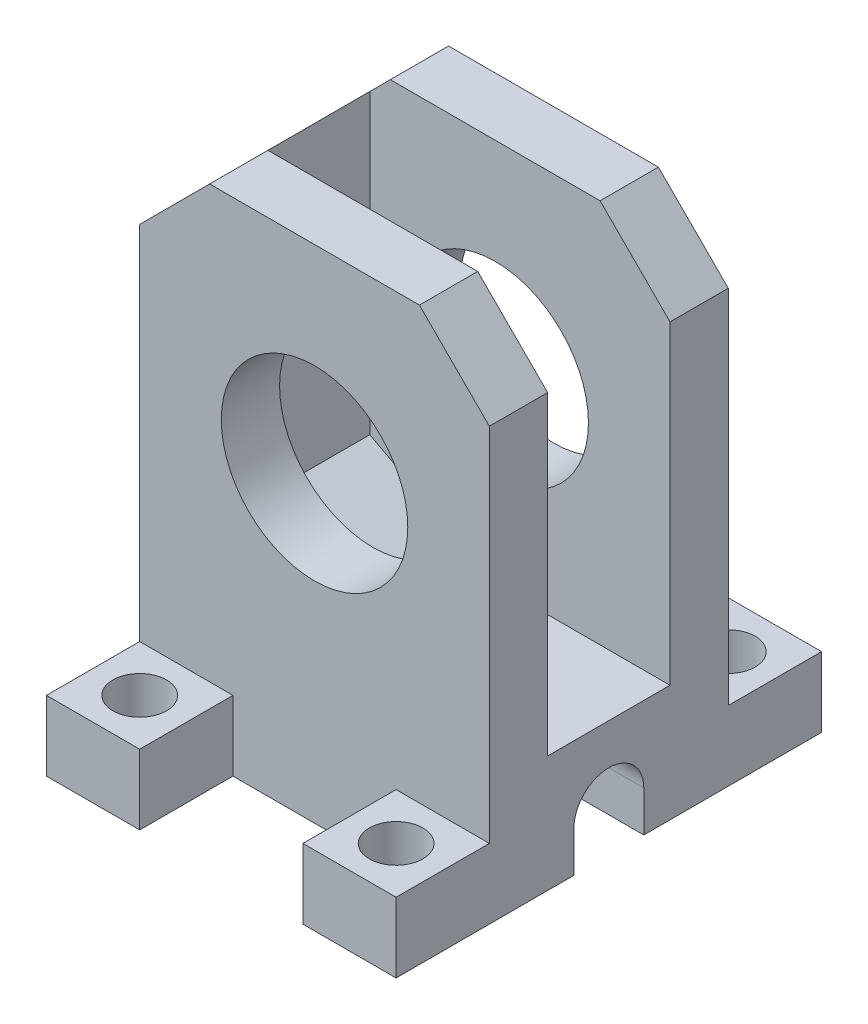
SolidWorks part; units mm, degrees
ref_plane "Plan de face" through (0, 0, 0) normal (0, 0, 1) x (1, 0, 0)
ref_plane "Plan de dessus" through (0, 0, 0) normal (0, 1, 0) x (1, 0, 0)
ref_plane "Plan de droite" through (0, 0, 0) normal (1, 0, 0) x (0, 0, -1)
sketch "Esquisse1" plane through (0, 0, 0) normal (0, 0, 1) x (1, 0, 0)
  line L0 (0, 0) -> (15, 0)
  line L1 (0, 0) -> (-15, 0)
  line L2 (-15, 0) -> (-15, 45)
  line L3 (-15, 45) -> (15, 45)
  line L4 (15, 45) -> (15, 0)
  line L5 (0, 0) -> (0, 28) construction
  circle A0 centre (0, 28) radius 8
  dimension "D1" = 28
extrude "Boss.-Extru.1" add sketch "Esquisse1" against normal blind 5
sketch "Esquisse2" plane through (0, 0, -5) normal (0, 0, -1) x (-1, 0, 0)
  line L0 (-15, 0) -> (15, 0)
  line L1 (15, 0) -> (15, 12)
  line L2 (15, 45) -> (15, 0) construction
  line L3 (15, 12) -> (-15, 12)
  line L4 (-15, 0) -> (-15, 45) construction
  line L5 (-15, 12) -> (-15, 0)
extrude "Boss.-Extru.2" add sketch "Esquisse2" along normal blind 10.5
sketch "Esquisse4" plane through (0, 0, 0) normal (0, -1, 0) x (1, 0, 0)
  line L0 (-15, -15.5) -> (15, -15.5)
  line L1 (15, -15.5) -> (15, -20.5)
  line L2 (15, -20.5) -> (-15, -20.5)
  line L3 (-15, -20.5) -> (-15, -15.5)
extrude "Boss.-Extru.3" add sketch "Esquisse4" against normal blind 45
sketch "Esquisse6" plane through (0, 0, -20.5) normal (0, 0, -1) x (-1, 0, 0)
  line L0 (0, 0) -> (0, 28) construction
  circle A1 centre (0, 28) radius 8
extrude "Enlèv. mat.-Extru.3" cut sketch "Esquisse6" against normal blind 10
sketch "Esquisse8" plane through (0, 0, 0) normal (0, -1, 0) x (1, 0, 0)
  line L0 (-15, 0) -> (-15, 8)
  line L1 (-15, 8) -> (-7, 8)
  line L2 (-7, 8) -> (-7, 0)
  line L3 (-15, 0) -> (15, 0) construction
  line L4 (-15, 0) -> (-7, 0)
  line L5 (15, 0) -> (15, 8)
  line L6 (15, 8) -> (7, 8)
  line L7 (7, 8) -> (7, 0)
  line L8 (7, 0) -> (15, 0)
  line L9 (-15, -20.5) -> (-15, -28.5)
  line L10 (-15, -28.5) -> (-7, -28.5)
  line L11 (-7, -28.5) -> (-7, -20.5)
  line L12 (-15, -20.5) -> (15, -20.5) construction
  line L13 (-7, -20.5) -> (-15, -20.5)
  line L14 (15, -20.5) -> (15, -28.5)
  line L15 (15, -28.5) -> (7, -28.5)
  line L16 (7, -28.5) -> (7, -20.5)
  line L17 (7, -20.5) -> (15, -20.5)
  line L18 (15, -28.5) -> (7, -20.5) construction
  line L19 (7, -28.5) -> (15, -20.5) construction
  line L20 (7, 8) -> (15, 0) construction
  line L21 (7, 0) -> (15, 8) construction
  line L22 (-15, 8) -> (-7, 0) construction
  line L23 (-7, 8) -> (-15, 0) construction
  line L24 (-15, -20.5) -> (-7, -28.5) construction
  line L25 (-15, -28.5) -> (-7, -20.5) construction
  circle A0 centre (-11, 4) radius 2.3
  circle A2 centre (11, -24.5) radius 2.3
  circle A3 centre (-11, -24.5) radius 2.3
  circle A4 centre (11, 4) radius 2.3
extrude "Boss.-Extru.4" add sketch "Esquisse8" against normal blind 8
sketch "Esquisse9" plane through (0, 0, 0) normal (0, -1, 0) x (1, 0, 0)
  line L0 (-15, 8) -> (-15, -28.5)
  line L1 (-15, -28.5) -> (-7, -28.5)
  line L2 (-7, -28.5) -> (-7, -20.5)
  line L3 (-7, -20.5) -> (7, -20.5)
  line L4 (7, -20.5) -> (7, -28.5)
  line L5 (7, -28.5) -> (15, -28.5)
  line L6 (15, -28.5) -> (15, 8)
  line L7 (15, 8) -> (7, 8)
  line L8 (7, 8) -> (7, 0) construction
  line L9 (15, 8) -> (7, 8) construction
  line L10 (7, 8) -> (7, 0)
  line L11 (7, 0) -> (-7, 0)
  line L12 (-7, 0) -> (-7, 8)
  line L13 (-7, 8) -> (-15, 8)
extrude "Enlèv. mat.-Extru.4" cut sketch "Esquisse9" against normal blind 2
sketch "Esquisse10" plane through (-15, 0, 0) normal (-1, 0, 0) x (0, 0, 1)
  line L0 (-10.25, 2) -> (-10.25, 5.5) construction
  line L1 (8, 2) -> (-28.5, 2) construction
  line L2 (-13.25, 5.5) -> (-13.25, 2)
  line L3 (-13.25, 2) -> (-7.25, 2)
  line L4 (-7.25, 2) -> (-7.25, 5.5)
  circle A0 centre (-10.25, 5.5) radius 3
extrude "Enlèv. mat.-Extru.5" cut sketch "Esquisse10" against normal blind 50
sketch "Esquisse11" plane through (0, 0, 0) normal (0, 0, 1) x (1, 0, 0)
  line L0 (-15, 45) -> (-15, 39)
  line L1 (-15, 45) -> (-15, 8) construction
  line L2 (-15, 45) -> (-9, 45)
  line L3 (15, 45) -> (-15, 45) construction
  line L4 (-9, 45) -> (-15, 39)
  line L5 (15, 45) -> (9, 45)
  line L6 (9, 45) -> (15, 45)
  line L7 (15, 45) -> (15, 39)
  line L8 (15, 8) -> (15, 45) construction
  line L9 (15, 39) -> (9, 45)
  line M8 (15, 8) -> (15, 45)
  line M9 (15, 45) -> (-15, 45)
  line M10 (-15, 45) -> (-15, 8)
extrude "Enlèv. mat.-Extru.6" cut sketch "Esquisse11" against normal blind 50 contours L4 M9 M10 | L9 M8 M9
sketch "Esquisse12" plane through (0, 0, -5) normal (0, 0, -1) x (-1, 0, 0)
  line L0 (0, 20) -> (0, 12) construction
  line L1 (0, 12) -> (15, 12)
  line L2 (15, 39) -> (15, 8) construction
  line L3 (15, 12) -> (15, 20)
  line L4 (15, 20) -> (0, 12)
  circle A0 centre (0, 28) radius 8 construction
extrude "Boss.-Extru.5" add sketch "Esquisse12" along normal blind 10.5
sketch "Esquisse13" plane through (0, 0, -15.5) normal (0, 0, 1) x (1, 0, 0)
  line L0 (-15, 20) -> (-15, 39)
  line L15 (-15, 39) -> (-10.7574, 43.2426)
  line L16 (-9, 45) -> (-15, 39) construction
  line L17 (-10.7574, 43.2426) -> (-10.7574, 17.084)
  line L18 (-15, 20) -> (-10.7574, 17.084)
extrude "Boss.-Extru.7" add sketch "Esquisse13" along normal blind 15
